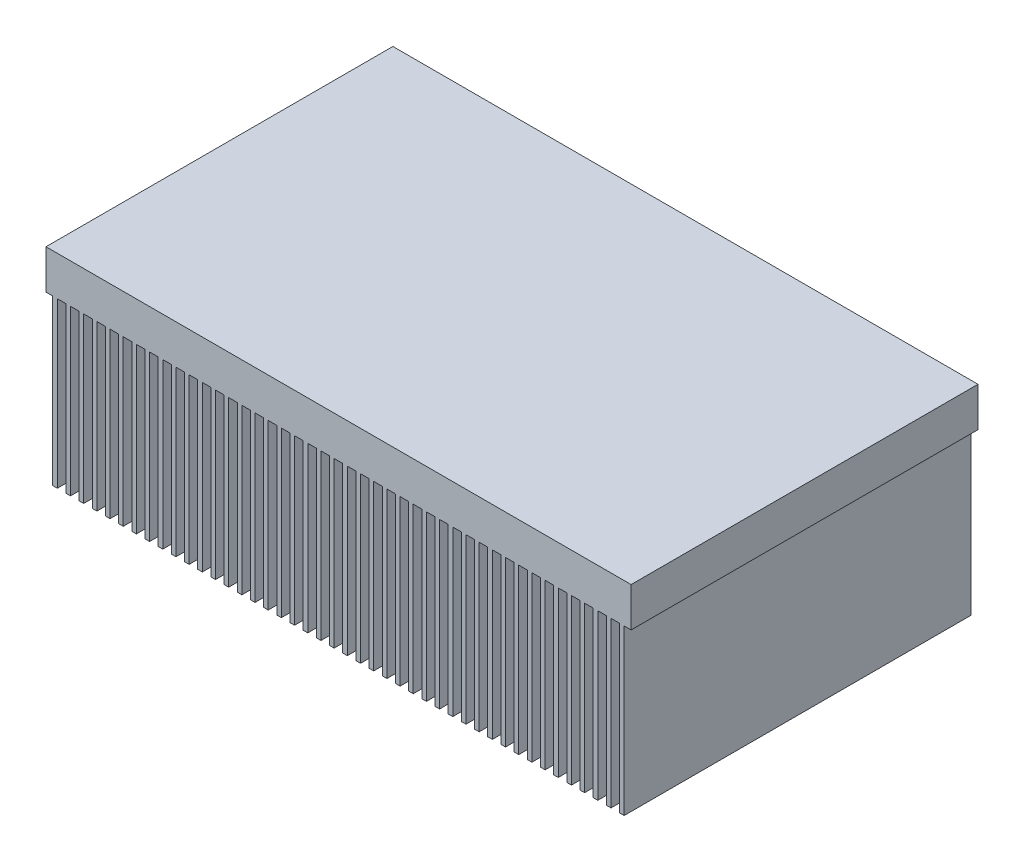
SolidWorks part; units mm, degrees
ref_plane "前视基准面" through (0, 0, 0) normal (0, 0, 1) x (1, 0, 0)
ref_plane "上视基准面" through (0, 0, 0) normal (0, 1, 0) x (1, 0, 0)
ref_plane "右视基准面" through (0, 0, 0) normal (1, 0, 0) x (0, 0, -1)
sketch "草图1" plane through (0, 0, 0) normal (0, 0, 1) x (1, 0, 0)
  line L0 (2.9, -17) -> (2.9, -88)
  line L1 (0, 0) -> (253, 0)
  line L2 (0, 0) -> (0, -17)
  line L3 (0, -17) -> (253, -17)
  line L4 (253, 0) -> (253, -17)
  line L5 (4.9, -17) -> (4.9, -88)
  line L6 (2.9, -88) -> (4.9, -88)
  line L7 (2.9, -17) -> (4.9, -17)
  line L8 (8.6, -17) -> (8.6, -88)
  line L9 (10.6, -17) -> (10.6, -88)
  line L10 (8.6, -88) -> (10.6, -88)
  line L11 (8.6, -17) -> (10.6, -17)
  line L12 (14.3, -17) -> (14.3, -88)
  line L13 (16.3, -17) -> (16.3, -88)
  line L14 (14.3, -88) -> (16.3, -88)
  line L15 (14.3, -17) -> (16.3, -17)
  line L16 (20, -17) -> (20, -88)
  line L17 (22, -17) -> (22, -88)
  line L18 (20, -88) -> (22, -88)
  line L19 (20, -17) -> (22, -17)
  line L20 (25.7, -17) -> (25.7, -88)
  line L21 (27.7, -17) -> (27.7, -88)
  line L22 (25.7, -88) -> (27.7, -88)
  line L23 (25.7, -17) -> (27.7, -17)
  line L24 (31.4, -17) -> (31.4, -88)
  line L25 (33.4, -17) -> (33.4, -88)
  line L26 (31.4, -88) -> (33.4, -88)
  line L27 (31.4, -17) -> (33.4, -17)
  line L28 (37.1, -17) -> (37.1, -88)
  line L29 (39.1, -17) -> (39.1, -88)
  line L30 (37.1, -88) -> (39.1, -88)
  line L31 (37.1, -17) -> (39.1, -17)
  line L32 (42.8, -17) -> (42.8, -88)
  line L33 (44.8, -17) -> (44.8, -88)
  line L34 (42.8, -88) -> (44.8, -88)
  line L35 (42.8, -17) -> (44.8, -17)
  line L36 (48.5, -17) -> (48.5, -88)
  line L37 (50.5, -17) -> (50.5, -88)
  line L38 (48.5, -88) -> (50.5, -88)
  line L39 (48.5, -17) -> (50.5, -17)
  line L40 (54.2, -17) -> (54.2, -88)
  line L41 (56.2, -17) -> (56.2, -88)
  line L42 (54.2, -88) -> (56.2, -88)
  line L43 (54.2, -17) -> (56.2, -17)
  line L44 (59.9, -17) -> (59.9, -88)
  line L45 (61.9, -17) -> (61.9, -88)
  line L46 (59.9, -88) -> (61.9, -88)
  line L47 (59.9, -17) -> (61.9, -17)
  line L48 (65.6, -17) -> (65.6, -88)
  line L49 (67.6, -17) -> (67.6, -88)
  line L50 (65.6, -88) -> (67.6, -88)
  line L51 (65.6, -17) -> (67.6, -17)
  line L52 (71.3, -17) -> (71.3, -88)
  line L53 (73.3, -17) -> (73.3, -88)
  line L54 (71.3, -88) -> (73.3, -88)
  line L55 (71.3, -17) -> (73.3, -17)
  line L56 (77, -17) -> (77, -88)
  line L57 (79, -17) -> (79, -88)
  line L58 (77, -88) -> (79, -88)
  line L59 (77, -17) -> (79, -17)
  line L60 (82.7, -17) -> (82.7, -88)
  line L61 (84.7, -17) -> (84.7, -88)
  line L62 (82.7, -88) -> (84.7, -88)
  line L63 (82.7, -17) -> (84.7, -17)
  line L64 (88.4, -17) -> (88.4, -88)
  line L65 (90.4, -17) -> (90.4, -88)
  line L66 (88.4, -88) -> (90.4, -88)
  line L67 (88.4, -17) -> (90.4, -17)
  line L68 (94.1, -17) -> (94.1, -88)
  line L69 (96.1, -17) -> (96.1, -88)
  line L70 (94.1, -88) -> (96.1, -88)
  line L71 (94.1, -17) -> (96.1, -17)
  line L72 (99.8, -17) -> (99.8, -88)
  line L73 (101.8, -17) -> (101.8, -88)
  line L74 (99.8, -88) -> (101.8, -88)
  line L75 (99.8, -17) -> (101.8, -17)
  line L76 (105.5, -17) -> (105.5, -88)
  line L77 (107.5, -17) -> (107.5, -88)
  line L78 (105.5, -88) -> (107.5, -88)
  line L79 (105.5, -17) -> (107.5, -17)
  line L80 (111.2, -17) -> (111.2, -88)
  line L81 (113.2, -17) -> (113.2, -88)
  line L82 (111.2, -88) -> (113.2, -88)
  line L83 (111.2, -17) -> (113.2, -17)
  line L84 (116.9, -17) -> (116.9, -88)
  line L85 (118.9, -17) -> (118.9, -88)
  line L86 (116.9, -88) -> (118.9, -88)
  line L87 (116.9, -17) -> (118.9, -17)
  line L88 (122.6, -17) -> (122.6, -88)
  line L89 (124.6, -17) -> (124.6, -88)
  line L90 (122.6, -88) -> (124.6, -88)
  line L91 (122.6, -17) -> (124.6, -17)
  line L92 (128.3, -17) -> (128.3, -88)
  line L93 (130.3, -17) -> (130.3, -88)
  line L94 (128.3, -88) -> (130.3, -88)
  line L95 (128.3, -17) -> (130.3, -17)
  line L96 (134, -17) -> (134, -88)
  line L97 (136, -17) -> (136, -88)
  line L98 (134, -88) -> (136, -88)
  line L99 (134, -17) -> (136, -17)
  line L100 (139.7, -17) -> (139.7, -88)
  line L101 (141.7, -17) -> (141.7, -88)
  line L102 (139.7, -88) -> (141.7, -88)
  line L103 (139.7, -17) -> (141.7, -17)
  line L104 (145.4, -17) -> (145.4, -88)
  line L105 (147.4, -17) -> (147.4, -88)
  line L106 (145.4, -88) -> (147.4, -88)
  line L107 (145.4, -17) -> (147.4, -17)
  line L108 (151.1, -17) -> (151.1, -88)
  line L109 (153.1, -17) -> (153.1, -88)
  line L110 (151.1, -88) -> (153.1, -88)
  line L111 (151.1, -17) -> (153.1, -17)
  line L112 (156.8, -17) -> (156.8, -88)
  line L113 (158.8, -17) -> (158.8, -88)
  line L114 (156.8, -88) -> (158.8, -88)
  line L115 (156.8, -17) -> (158.8, -17)
  line L116 (162.5, -17) -> (162.5, -88)
  line L117 (164.5, -17) -> (164.5, -88)
  line L118 (162.5, -88) -> (164.5, -88)
  line L119 (162.5, -17) -> (164.5, -17)
  line L120 (168.2, -17) -> (168.2, -88)
  line L121 (170.2, -17) -> (170.2, -88)
  line L122 (168.2, -88) -> (170.2, -88)
  line L123 (168.2, -17) -> (170.2, -17)
  line L124 (173.9, -17) -> (173.9, -88)
  line L125 (175.9, -17) -> (175.9, -88)
  line L126 (173.9, -88) -> (175.9, -88)
  line L127 (173.9, -17) -> (175.9, -17)
  line L128 (179.6, -17) -> (179.6, -88)
  line L129 (181.6, -17) -> (181.6, -88)
  line L130 (179.6, -88) -> (181.6, -88)
  line L131 (179.6, -17) -> (181.6, -17)
  line L132 (185.3, -17) -> (185.3, -88)
  line L133 (187.3, -17) -> (187.3, -88)
  line L134 (185.3, -88) -> (187.3, -88)
  line L135 (185.3, -17) -> (187.3, -17)
  line L136 (191, -17) -> (191, -88)
  line L137 (193, -17) -> (193, -88)
  line L138 (191, -88) -> (193, -88)
  line L139 (191, -17) -> (193, -17)
  line L140 (196.7, -17) -> (196.7, -88)
  line L141 (198.7, -17) -> (198.7, -88)
  line L142 (196.7, -88) -> (198.7, -88)
  line L143 (196.7, -17) -> (198.7, -17)
  line L144 (202.4, -17) -> (202.4, -88)
  line L145 (204.4, -17) -> (204.4, -88)
  line L146 (202.4, -88) -> (204.4, -88)
  line L147 (202.4, -17) -> (204.4, -17)
  line L148 (208.1, -17) -> (208.1, -88)
  line L149 (210.1, -17) -> (210.1, -88)
  line L150 (208.1, -88) -> (210.1, -88)
  line L151 (208.1, -17) -> (210.1, -17)
  line L152 (213.8, -17) -> (213.8, -88)
  line L153 (215.8, -17) -> (215.8, -88)
  line L154 (213.8, -88) -> (215.8, -88)
  line L155 (213.8, -17) -> (215.8, -17)
  line L156 (219.5, -17) -> (219.5, -88)
  line L157 (221.5, -17) -> (221.5, -88)
  line L158 (219.5, -88) -> (221.5, -88)
  line L159 (219.5, -17) -> (221.5, -17)
  line L160 (225.2, -17) -> (225.2, -88)
  line L161 (227.2, -17) -> (227.2, -88)
  line L162 (225.2, -88) -> (227.2, -88)
  line L163 (225.2, -17) -> (227.2, -17)
  line L164 (230.9, -17) -> (230.9, -88)
  line L165 (232.9, -17) -> (232.9, -88)
  line L166 (230.9, -88) -> (232.9, -88)
  line L167 (230.9, -17) -> (232.9, -17)
  line L168 (236.6, -17) -> (236.6, -88)
  line L169 (238.6, -17) -> (238.6, -88)
  line L170 (236.6, -88) -> (238.6, -88)
  line L171 (236.6, -17) -> (238.6, -17)
  line L172 (242.3, -17) -> (242.3, -88)
  line L173 (244.3, -17) -> (244.3, -88)
  line L174 (242.3, -88) -> (244.3, -88)
  line L175 (242.3, -17) -> (244.3, -17)
  line L176 (248, -17) -> (248, -88)
  line L177 (250, -17) -> (250, -88)
  line L178 (248, -88) -> (250, -88)
  line L179 (248, -17) -> (250, -17)
  point P7 (0, -8.5)
  point P8 (253, -8.5)
  dimension "D1" = 2.9
  dimension "D2" = 253
  dimension "D3" = 17
  dimension "D4" = 88
  dimension "D5" = 2
  dimension "D6" = 44
extrude "凸台-拉伸1" add sketch "草图1" along normal blind 150 contours L4 L1 L2 L3 | L0 L6 L5 L7 | L8 L10 L9 L11 | L13 L14 L12 L15 | L17 L18 L16 L19 | L20 L22 L21 L23 | L24 L26 L25 L27 | L28 L30 L29 L31 | L32 L34 L33 L35 | L36 L38 L37 L39 | L40 L42 L41 L43 | L44 L46 L45 L47 | L48 L50 L49 L51 | L52 L54 L53 L55 | L57 L58 L56 L59 | L60 L62 L61 L63 | L65 L66 L64 L67 | L68 L70 L69 L71 | L72 L74 L73 L75 | L76 L78 L77 L79 | L80 L82 L81 L83 | L84 L86 L85 L87 | L89 L90 L88 L91 | L92 L94 L93 L95 | L96 L98 L97 L99 | L100 L102 L101 L103 | L104 L106 L105 L107 | L108 L110 L109 L111 | L112 L114 L113 L115 | L116 L118 L117 L119 | L120 L122 L121 L123 | L124 L126 L125 L127 | L128 L130 L129 L131 | L133 L134 L132 L135 | L136 L138 L137 L139 | L140 L142 L141 L143 | L144 L146 L145 L147 | L148 L150 L149 L151 | L153 L154 L152 L155 | L156 L158 L157 L159 | L160 L162 L161 L163 | L164 L166 L165 L167 | L168 L170 L169 L171 | L172 L174 L173 L175 | L176 L178 L177 L179
